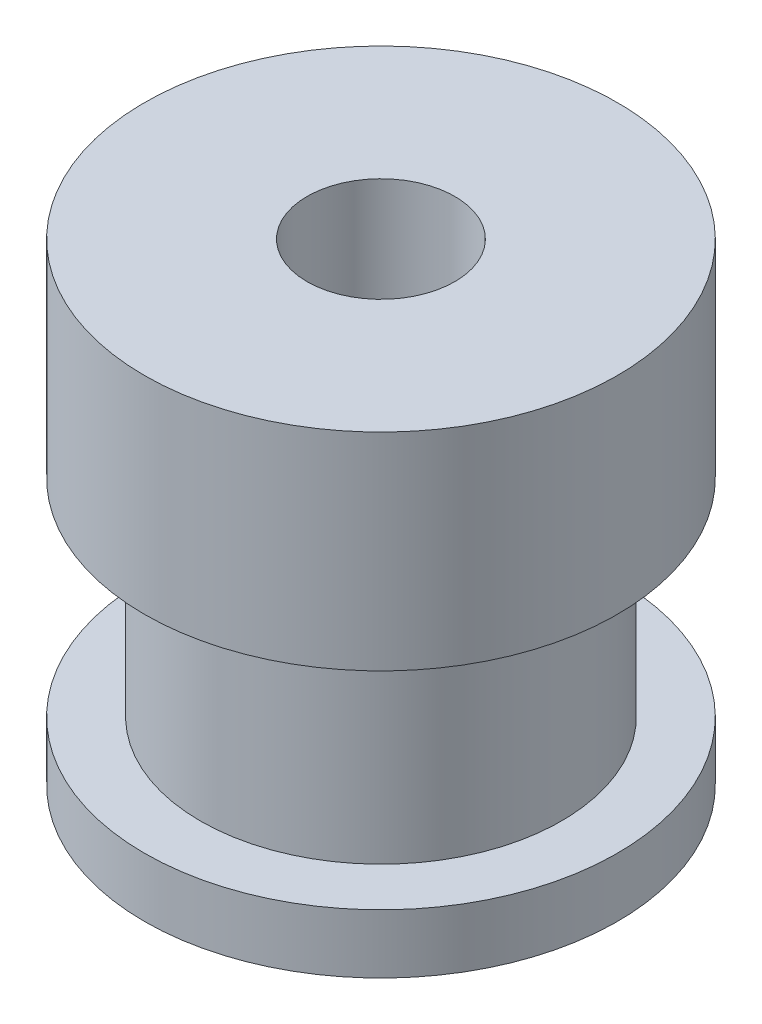
SolidWorks part; units mm, degrees
material "1060 合金"
ref_plane "前视基准面" through (0, 0, 0) normal (0, 0, 1) x (1, 0, 0)
ref_plane "上视基准面" through (0, 0, 0) normal (0, 1, 0) x (1, 0, 0)
ref_plane "右视基准面" through (0, 0, 0) normal (1, 0, 0) x (0, 0, -1)
other "Configuration Table"
sketch "草图1" plane through (0, 0, 0) normal (0, 1, 0) x (1, 0, 0)
  circle A0 centre (0, 0) radius 8
  dimension "D1" = 16
extrude "凸台-拉伸1" add sketch "草图1" along normal blind 2
sketch "草图2" plane through (0, 2, 0) normal (0, 1, 0) x (1, 0, 0)
  circle A0 centre (0, 0) radius 6.11
  dimension "D1" = 12.22
extrude "凸台-拉伸2" add sketch "草图2" along normal blind 7
sketch "草图3" plane through (0, 9, 0) normal (0, 1, 0) x (1, 0, 0)
  circle A0 centre (0, 0) radius 8
  dimension "D1" = 16
extrude "凸台-拉伸3" add sketch "草图3" along normal blind 7
sketch "草图4" plane through (0, 16, 0) normal (0, 1, 0) x (1, 0, 0)
  circle A0 centre (0, 0) radius 2.5
  dimension "D1" = 5
extrude "切除-拉伸1" cut sketch "草图4" against normal blind 24
